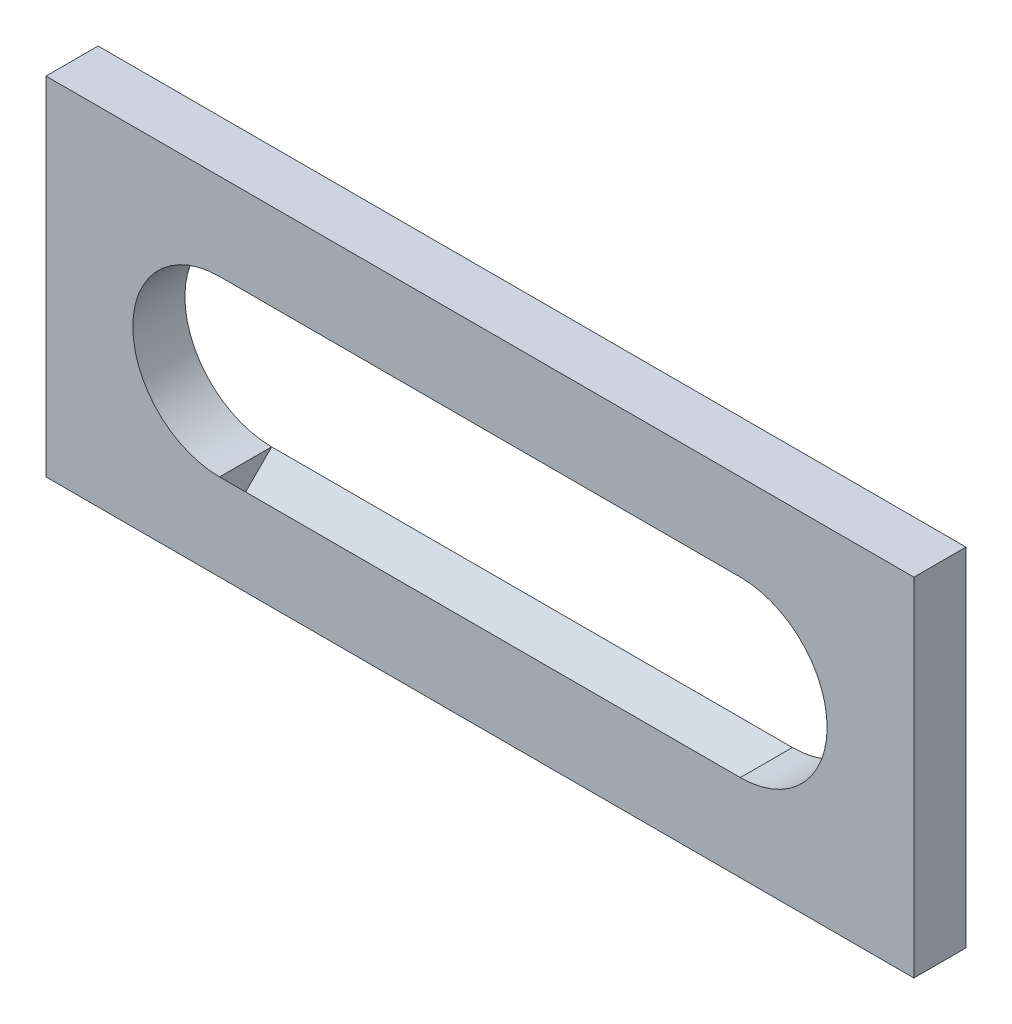
SolidWorks part; units mm, degrees
ref_plane "정면" through (0, 0, 0) normal (0, 0, 1) x (1, 0, 0)
ref_plane "윗면" through (0, 0, 0) normal (0, 1, 0) x (1, 0, 0)
ref_plane "우측면" through (0, 0, 0) normal (1, 0, 0) x (0, 0, -1)
sketch "스케치1" plane through (0, 0, 0) normal (0, 0, 1) x (1, 0, 0)
  line L1 (-25, -10) -> (25, -10)
  line L2 (-25, -10) -> (-25, 10)
  line L3 (-25, 10) -> (25, 10)
  line L4 (25, -10) -> (25, 10)
  line L5 (-25, -10) -> (25, 10) construction
  line L6 (-25, 10) -> (25, -10) construction
  line L7 (-15, -5) -> (15, -5)
  line L8 (-15, -5) -> (-15, 5)
  line L9 (-15, 5) -> (15, 5)
  line L10 (15, -5) -> (15, 5)
  line L11 (-15, -5) -> (15, 5) construction
  line L12 (-15, 5) -> (15, -5) construction
  circle A0 centre (-15, 0.0396) radius 5
  circle A1 centre (15, 0) radius 5
  point P0 (0, 0)
  point P10 (0, 0)
  dimension "D1" = 10
  dimension "10" = 10
  dimension "D2" = 10
  dimension "D3" = 30
  dimension "D4" = 0
  dimension "D5" = 0
  dimension "D6" = 50
  dimension "D7" = 20
extrude "보스-돌출3" add sketch "스케치1" along normal blind 3 contours L3 L4 L1 L2
sketch "스케치2" plane through (0, 0, 3) normal (0, 0, 1) x (1, 0, 0)
  line L1 (-15, -5) -> (15, -5)
  line L2 (-15, -5) -> (-15, 5)
  line L3 (-15, 5) -> (15, 5)
  line L4 (15, -5) -> (15, 5)
  line L5 (-15, -5) -> (15, 5) construction
  line L6 (-15, 5) -> (15, -5) construction
  circle A0 centre (-15, 0) radius 5
  circle A1 centre (15, 0) radius 5
  point P0 (0, 0)
  dimension "D2" = 10
  dimension "D1" = 30
extrude "컷-돌출1" cut sketch "스케치2" against normal blind 3 contours A0 | L3 L4 L1 L2 | A1
sketch "스케치3" plane through (0, 5, 0) normal (0, -1, 0) x (1, 0, 0)
  line L0 (-15, 0) -> (15, 0) construction
  line L1 (15, 0) -> (-15, 0)
  line L2 (15, 0) -> (15, 3)
  line L3 (15, 3) -> (-15, 3)
  line L4 (-15, 0) -> (-15, 3)
  line L5 (15, 0) -> (-15, 3) construction
  line L6 (15, 3) -> (-15, 0) construction
  point P0 (0, 1.5)
  point P7 (0, 0)
  dimension "D1" = 1.5
  dimension "D2" = 30
  dimension "D3" = 3
extrude "컷-돌출2" cut sketch "스케치3" against normal blind 1.5
sketch "스케치4" plane through (-15, 0, 0) normal (1, 0, 0) x (0, 0, -1)
  line L0 (-3, 5) -> (-1.5, 6.5)
  line L1 (-3, 6.5) -> (0, 6.5) construction
  line L2 (-1.5, 6.5) -> (0, 5)
  line M2 (0, 5) -> (0, 6.5)
  line M3 (0, 6.5) -> (-3, 6.5)
  line M4 (-3, 6.5) -> (-3, 5)
extrude "보스-돌출4" add sketch "스케치4" along normal up to next contours L0 M4 M3 | L2 M3 M2
sketch "스케치5" plane through (0, -5, 0) normal (0, 1, 0) x (1, 0, 0)
  line L0 (15, 0) -> (15, -3) construction
  line L1 (-15, -3) -> (15, -3)
  line L2 (-15, -3) -> (-15, 0)
  line L3 (-15, 0) -> (15, 0)
  line L4 (15, -3) -> (15, 0)
  line L5 (-15, -3) -> (15, 0) construction
  line L6 (-15, 0) -> (15, -3) construction
  line L7 (-15, 0) -> (15, 0) construction
  point P0 (0, -1.5)
  point P9 (0, 0)
  dimension "D1" = 3
  dimension "D2" = 1.5
extrude "컷-돌출3" cut sketch "스케치5" against normal blind 1.5
sketch "스케치6" plane through (-15, 0, 0) normal (1, 0, 0) x (0, 0, -1)
  line L0 (-3, -5) -> (-1.5, -6.5)
  line L1 (0, -6.5) -> (-3, -6.5) construction
  line L2 (-1.5, -6.5) -> (0, -5)
  line L7 (0, -5) -> (-3, -5)
  line L8 (-3, -5) -> (-3, -6.5)
  line L9 (-3, -6.5) -> (0, -6.5)
  line L10 (0, -6.5) -> (0, -5)
  line L12 (-3, -5) -> (-3, -6.5)
  line L13 (-3, -6.5) -> (0, -6.5)
  line L14 (0, -6.5) -> (0, -5)
  line M6 (-3, -5) -> (-3, -6.5)
  line M7 (-3, -6.5) -> (0, -6.5)
  line M8 (0, -6.5) -> (0, -5)
  dimension "D1" = 0
extrude "보스-돌출5" add sketch "스케치6" along normal up to next contours L0 M6 M7 | L2 M7 M8
